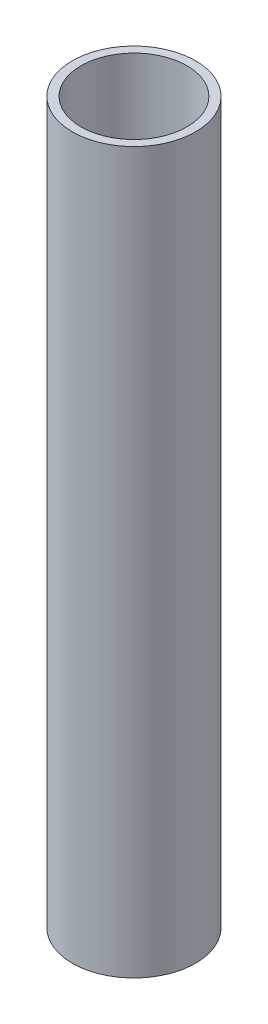
SolidWorks part; units mm, degrees
ref_plane "Front Plane" through (0, 0, 0) normal (0, 0, 1) x (1, 0, 0)
ref_plane "Top Plane" through (0, 0, 0) normal (0, 1, 0) x (1, 0, 0)
ref_plane "Right Plane" through (0, 0, 0) normal (1, 0, 0) x (0, 0, -1)
sketch "Sketch1" plane through (0, 0, 0) normal (0, 1, 0) x (1, 0, 0)
  circle A0 centre (0, 0) radius 21.1
  circle A1 centre (0, 0) radius 18.15
  dimension "D1" = 42.2
  dimension "D2" = 36.3
extrude "Boss-Extrude1" add sketch "Sketch1" along normal mid plane 246.6
